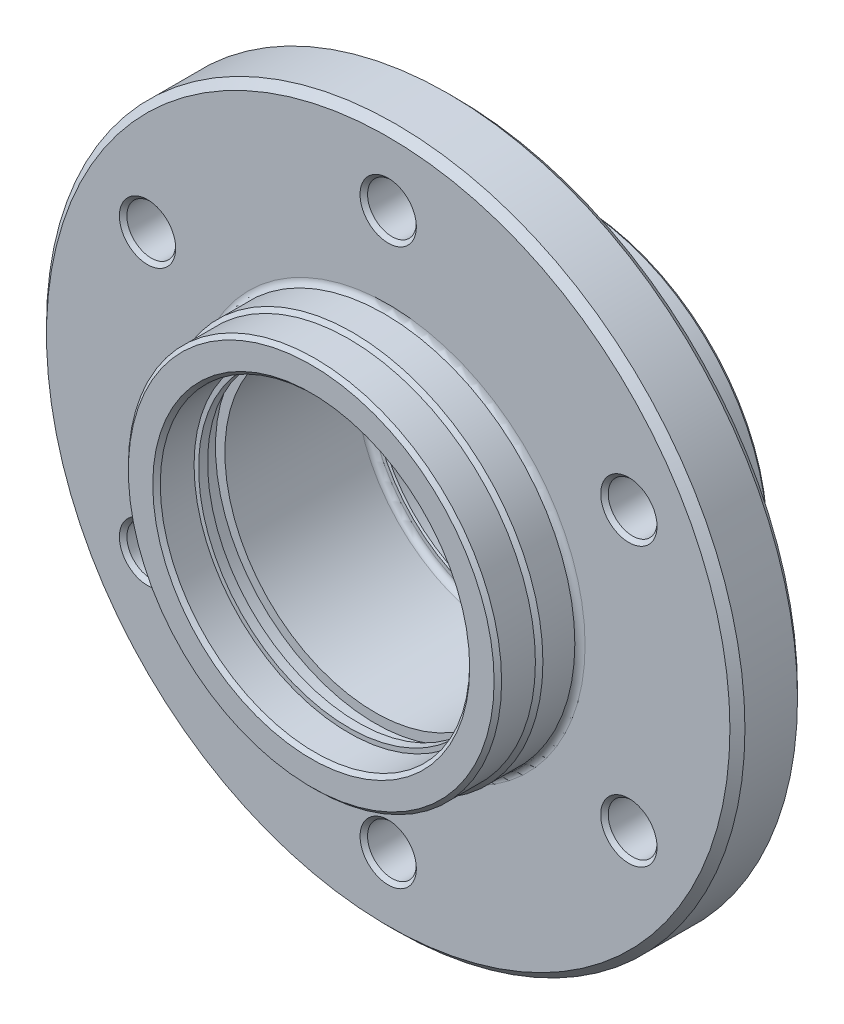
SolidWorks part; units mm, degrees
material "AISI 1010 Barra de acero laminada en caliente"
ref_plane "Alzado" through (0, 0, 0) normal (0, 0, 1) x (1, 0, 0)
ref_plane "Planta" through (0, 0, 0) normal (0, 1, 0) x (1, 0, 0)
ref_plane "Vista lateral" through (0, 0, 0) normal (1, 0, 0) x (0, 0, -1)
sketch "Croquis1" plane through (0, 0, 0) normal (1, 0, 0) x (0, 0, -1)
  line L0 (-23.3026, 0) -> (24.4926, 0) construction
  line L7 (-9, 26.216) -> (-9, 45.5)
  line L8 (-8, 46.5) -> (-1, 46.5)
  line L9 (0, 45.5) -> (0, 26)
  line L10 (0.6, 26) -> (15.45, 26)
  line L21 (-9, 45.5) -> (-8, 46.5)
  line L22 (-1, 46.5) -> (0, 45.5)
  line L34 (10.95, 18.7) -> (10.75, 18.5)
  line L37 (-13.75, 25.35) -> (-14.25, 24.85)
  line L38 (7.45, 18.7) -> (7.65, 18.5)
  line L39 (-13.05, 20) -> (-13.05, 21.25)
  line L40 (-13.05, 21.25) -> (-10.75, 21.25)
  line L41 (-10.75, 21.25) -> (-10.75, 20)
  line L42 (7.65, 18.5) -> (10.75, 18.5)
  line L45 (-10.75, 20) -> (6.65, 20)
  line L46 (-14.25, 20) -> (-13.05, 20)
  line L47 (7.45, 18.7) -> (7.45, 19.2)
  line L48 (-14.25, 24.85) -> (-18.75, 24.85)
  line L62 (10.95, 18.7) -> (10.95, 20.6)
  line L63 (10.95, 20.6) -> (15.45, 20.6)
  line L65 (15.45, 20.6) -> (15.95, 21.1)
  line L66 (15.95, 21.1) -> (15.95, 25.5)
  line L68 (15.45, 26) -> (15.95, 25.5)
  line L70 (-14.25, 20) -> (-14.25, 20.6)
  line L71 (-14.25, 20.6) -> (-18.75, 20.6)
  line L72 (-19.25, 21.1) -> (-19.25, 24.35)
  line L74 (-13.75, 25.35) -> (-9.5, 25.35)
  line L75 (-18.75, 20.6) -> (-19.25, 21.1)
  line L76 (-18.75, 24.85) -> (-19.25, 24.35)
  arc A1 (0, 26) -> (0.6, 26) centre (0.3, 26) ccw
  arc A3 (7.45, 19.2) -> (6.65, 20) centre (6.65, 19.2) ccw
  arc A5 (-9, 26.216) -> (-9.5, 25.35) centre (-10, 26.216) cw
  point P4 (0, 0)
  point P11 (-9, 46.5)
  point P12 (0, 46.5)
  dimension "D18" = 0.5
  dimension "D19" = 0.2
  dimension "D5" = 25.35
  dimension "D12" = 0.8
  dimension "D29" = 0.5
  dimension "D8" = 0.2
  dimension "D7" = 1
  dimension "D3" = 26
  dimension "D4" = 15.95
  dimension "D6" = 0.5
  dimension "D9" = 46.5
  dimension "D10" = 0.2
  dimension "D11" = 9
  dimension "D13" = 20
  dimension "D14" = 0.5
  dimension "D15" = 0.5
  dimension "D16" = 37
  dimension "D17" = 45
  dimension "D22" = 0.3
  dimension "D23" = 0.5
  dimension "D24" = 1
  dimension "D25" = 1.2
  dimension "D26" = 42.5
  dimension "D27" = 2.3
  dimension "D28" = 18.2
  dimension "D32" = 20.6
  dimension "D34" = 0.5
  dimension "D30" = 5
  dimension "D31" = 5
  dimension "D33" = 3.5
  dimension "D36" = 35.2
  dimension "D37" = 0.5
  dimension "D38" = 0.5
  dimension "D39" = 5
revolve "Revolución1" add sketch "Croquis1" angle 360 about L0
sketch "Croquis2" plane through (0, 0, 9) normal (0, 0, 1) x (1, 0, 0)
  circle A1 centre (0, 37) radius 3.25
  circle A2 centre (32.0429, 18.5) radius 3.25
  circle A3 centre (32.0429, -18.5) radius 3.25
  circle A4 centre (0, -37) radius 3.25
  circle A5 centre (-32.0429, -18.5) radius 3.25
  circle A6 centre (-32.0429, 18.5) radius 3.25
  circle A7 centre (0, 0) radius 37 construction
  point P18 (0, 0)
  dimension "D1" = 74
  dimension "D2" = 6.5
  dimension "D3" = 6
extrude "Cortar-Extruir1" cut sketch "Croquis2" against normal through all
chamfer "Chaflán1" distance 0.5 angle 45 12 edges at (-35.2929, -18.5, 0) (-3.25, -37, 0) (28.7929, -18.5, 0) (28.7929, 18.5, 0) (-3.25, 37, 0) (-35.2929, 18.5, 0) (-28.7929, 18.5, 9) (-28.7929, -18.5, 9) (3.25, -37, 9) (35.2929, -18.5, 9) (35.2929, 18.5, 9) (3.25, 37, 9)
